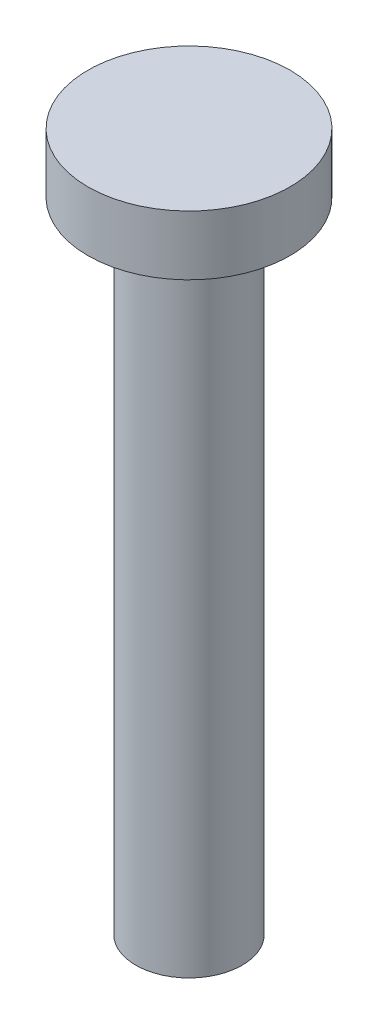
SolidWorks part; units mm, degrees
ref_plane "Front Plane" through (0, 0, 0) normal (0, 0, 1) x (1, 0, 0)
ref_plane "Top Plane" through (0, 0, 0) normal (0, 1, 0) x (1, 0, 0)
ref_plane "Right Plane" through (0, 0, 0) normal (1, 0, 0) x (0, 0, -1)
sketch "Sketch1" plane through (0, 0, 0) normal (0, 0, 1) x (1, 0, 0)
  line L0 (0, -30) -> (2.5, -30)
  line L1 (2.5, -30) -> (2.5, 0)
  line L2 (2.5, 0) -> (4.75, 0)
  line L3 (4.75, 0) -> (4.75, 2.8)
  line L4 (4.75, 2.8) -> (0, 2.8)
  line L5 (0, 2.8) -> (0, -30)
  line L6 (0, -10) -> (0, 1000) construction
revolve "Revolve1" add sketch "Sketch1" angle 360 about L6
